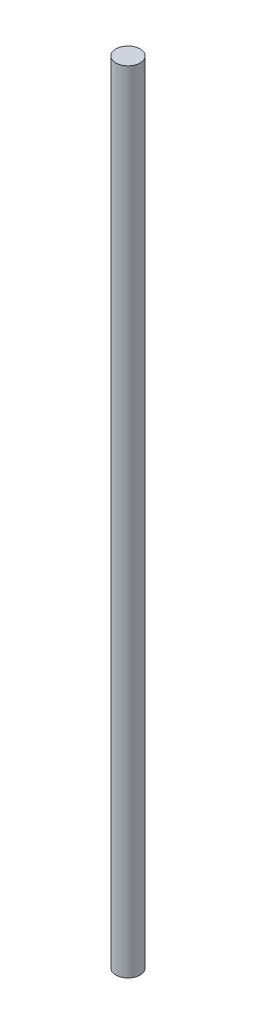
SolidWorks part; units mm, degrees
ref_plane "Front Plane" through (0, 0, 0) normal (0, 0, 1) x (1, 0, 0)
ref_plane "Top Plane" through (0, 0, 0) normal (0, 1, 0) x (1, 0, 0)
ref_plane "Right Plane" through (0, 0, 0) normal (1, 0, 0) x (0, 0, -1)
sketch "Sketch1" plane through (0, 0, 0) normal (0, 1, 0) x (1, 0, 0)
  circle A0 centre (0, 0) radius 5
  dimension "D1" = 10
extrude "Boss-Extrude1" add sketch "Sketch1" along normal blind 325
